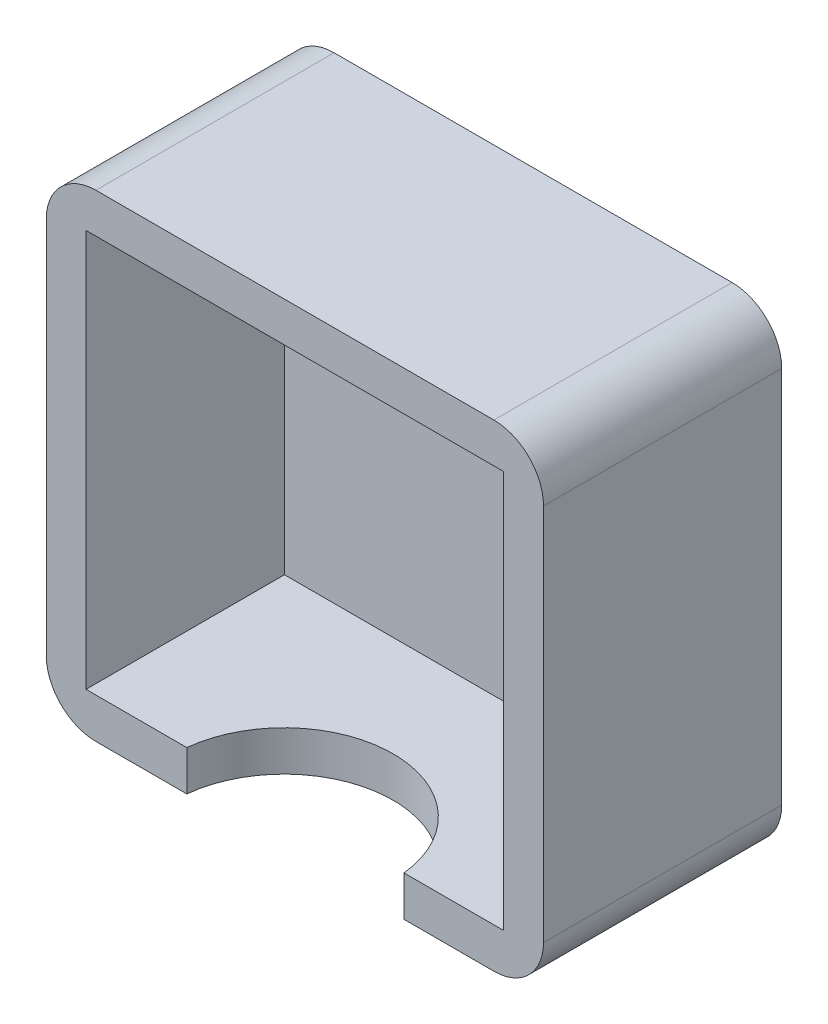
SolidWorks part; units mm, degrees
ref_plane "Plano frontal" through (0, 0, 0) normal (0, 0, 1) x (1, 0, 0)
ref_plane "Plano superior" through (0, 0, 0) normal (0, 1, 0) x (1, 0, 0)
ref_plane "Plano direito" through (0, 0, 0) normal (1, 0, 0) x (0, 0, -1)
sketch "Esboço1" plane through (0, 0, 0) normal (0, 0, 1) x (1, 0, 0)
  line L1 (-27.1496, 15.8365) -> (22.9504, 15.8365)
  line L2 (-27.1496, 15.8365) -> (-27.1496, -32.2635)
  line L3 (-27.1496, -32.2635) -> (22.9504, -32.2635)
  line L4 (22.9504, 15.8365) -> (22.9504, -32.2635)
  line L5 (-23.1496, 11.8365) -> (18.9004, 11.8365)
  line L6 (-23.1496, 11.8365) -> (-23.1496, -28.2135)
  line L7 (-23.1496, -28.2135) -> (18.9004, -28.2135)
  line L8 (18.9004, 11.8365) -> (18.9004, -28.2135)
  dimension "D1" = 50.1
  dimension "D2" = 48.1
  dimension "D3" = 42.05
  dimension "D4" = 40.05
  dimension "D5" = 4
  dimension "D6" = 4
extrude "Ressalto-extrusão1" add sketch "Esboço1" along normal blind 20
sketch "Esboço3" plane through (0, 0, 0) normal (0, 0, -1) x (-1, 0, 0)
  line L1 (-22.9504, 15.8365) -> (27.1496, 15.8365)
  line L2 (-22.9504, 15.8365) -> (-22.9504, -32.2635)
  line L3 (-22.9504, -32.2635) -> (27.1496, -32.2635)
  line L4 (27.1496, 15.8365) -> (27.1496, -32.2635)
extrude "Ressalto-extrusão3" add sketch "Esboço3" along normal blind 4
sketch "Esboço4" plane through (0, -32.2635, 0) normal (0, -1, 0) x (1, 0, 0)
  line L0 (-2.0996, -4) -> (-2.0996, 20) construction
  line L1 (22.9504, -4) -> (-27.1496, -4) construction
  line L2 (-27.1496, 20) -> (22.9504, 20) construction
  line L3 (-23.1496, 0) -> (18.9004, 0) construction
  circle A0 centre (-2.0496, 21.15) radius 11
  dimension "D2" = 22
  dimension "D1" = 21.15
extrude "Corte-extrusão1" cut sketch "Esboço4" against normal blind 14
fillet "Filete2" radius 5 4 edges at (22.9504, 15.8365, 8) (-27.1496, 15.8365, 8) (-27.1496, -32.2635, 8) (22.9504, -32.2635, 8)
